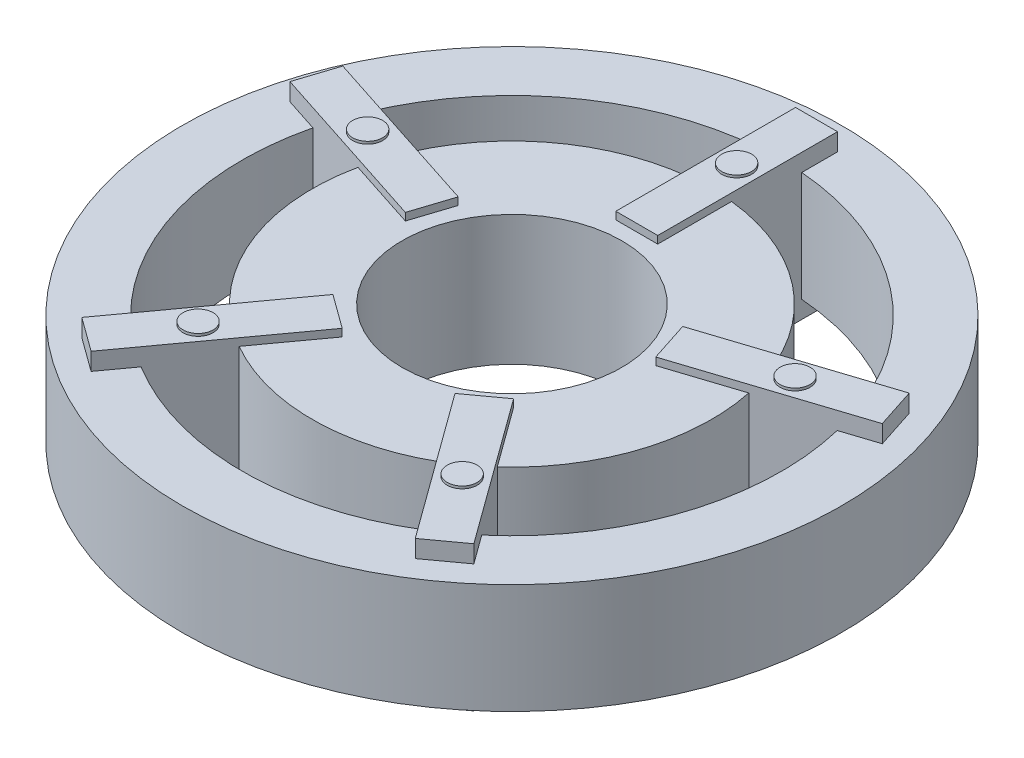
SolidWorks part; units mm, degrees
ref_plane "Front Plane" through (0, 0, 0) normal (0, 0, 1) x (1, 0, 0)
ref_plane "Top Plane" through (0, 0, 0) normal (0, 1, 0) x (1, 0, 0)
ref_plane "Right Plane" through (0, 0, 0) normal (1, 0, 0) x (0, 0, -1)
sketch "Sketch1" plane through (0, 0, 0) normal (0, 1, 0) x (1, 0, 0)
  circle A0 centre (0, 0) radius 66
  circle A1 centre (0, 0) radius 54
extrude "rim outer ring" add sketch "Sketch1" along normal mid plane 22
sketch "Sketch2" plane through (0, 0, 0) normal (0, 1, 0) x (1, 0, 0)
  circle A0 centre (0, 0) radius 40
  circle A1 centre (0, 0) radius 22
extrude "rim hub ring" add sketch "Sketch2" along normal mid plane 26
sketch "Sketch3" plane through (0, 0, 0) normal (0, 1, 0) x (1, 0, 0)
  line L0 (22.4785, 11.7199) -> (56.7166, 22.8445)
  line L1 (56.7166, 22.8445) -> (59.3123, 14.8556)
  line L2 (59.3123, 14.8556) -> (25.0743, 3.731)
  line L3 (25.0743, 3.731) -> (22.4785, 11.7199)
extrude "rim spoke 1" add sketch "Sketch3" along normal mid plane 29
sketch "Sketch4" plane through (0, 0, 0) normal (0, 1, 0) x (1, 0, 0)
  circle A0 centre (42.7975, 13.9058) radius 3
extrude "rim bolt pad 1" add sketch "Sketch4" along normal mid plane 30
sketch "Sketch5" plane through (0, 0, 0) normal (0, 1, 0) x (1, 0, 0)
  line L0 (-4.2, 25) -> (-4.2, 61)
  line L1 (-4.2, 61) -> (4.2, 61)
  line L2 (4.2, 61) -> (4.2, 25)
  line L3 (4.2, 25) -> (-4.2, 25)
extrude "rim spoke 2" add sketch "Sketch5" along normal mid plane 29
sketch "Sketch6" plane through (0, 0, 0) normal (0, 1, 0) x (1, 0, 0)
  circle A0 centre (0, 45) radius 3
extrude "rim bolt pad 2" add sketch "Sketch6" along normal mid plane 30
sketch "Sketch7" plane through (0, 0, 0) normal (0, 1, 0) x (1, 0, 0)
  line L0 (-25.0743, 3.731) -> (-59.3123, 14.8556)
  line L1 (-59.3123, 14.8556) -> (-56.7166, 22.8445)
  line L2 (-56.7166, 22.8445) -> (-22.4785, 11.7199)
  line L3 (-22.4785, 11.7199) -> (-25.0743, 3.731)
extrude "rim spoke 3" add sketch "Sketch7" along normal mid plane 29
sketch "Sketch8" plane through (0, 0, 0) normal (0, 1, 0) x (1, 0, 0)
  circle A0 centre (-42.7975, 13.9058) radius 3
extrude "rim bolt pad 3" add sketch "Sketch8" along normal mid plane 30
sketch "Sketch9" plane through (0, 0, 0) normal (0, 1, 0) x (1, 0, 0)
  line L0 (-11.2968, -22.6941) -> (-32.457, -51.8187)
  line L1 (-32.457, -51.8187) -> (-39.2528, -46.8813)
  line L2 (-39.2528, -46.8813) -> (-18.0925, -17.7567)
  line L3 (-18.0925, -17.7567) -> (-11.2968, -22.6941)
extrude "rim spoke 4" add sketch "Sketch9" along normal mid plane 29
sketch "Sketch10" plane through (0, 0, 0) normal (0, 1, 0) x (1, 0, 0)
  circle A0 centre (-26.4503, -36.4058) radius 3
extrude "rim bolt pad 4" add sketch "Sketch10" along normal mid plane 30
sketch "Sketch11" plane through (0, 0, 0) normal (0, 1, 0) x (1, 0, 0)
  line L0 (18.0925, -17.7567) -> (39.2528, -46.8813)
  line L1 (39.2528, -46.8813) -> (32.457, -51.8187)
  line L2 (32.457, -51.8187) -> (11.2968, -22.6941)
  line L3 (11.2968, -22.6941) -> (18.0925, -17.7567)
extrude "rim spoke 5" add sketch "Sketch11" along normal mid plane 29
sketch "Sketch12" plane through (0, 0, 0) normal (0, 1, 0) x (1, 0, 0)
  circle A0 centre (26.4503, -36.4058) radius 3
extrude "rim bolt pad 5" add sketch "Sketch12" along normal mid plane 30
